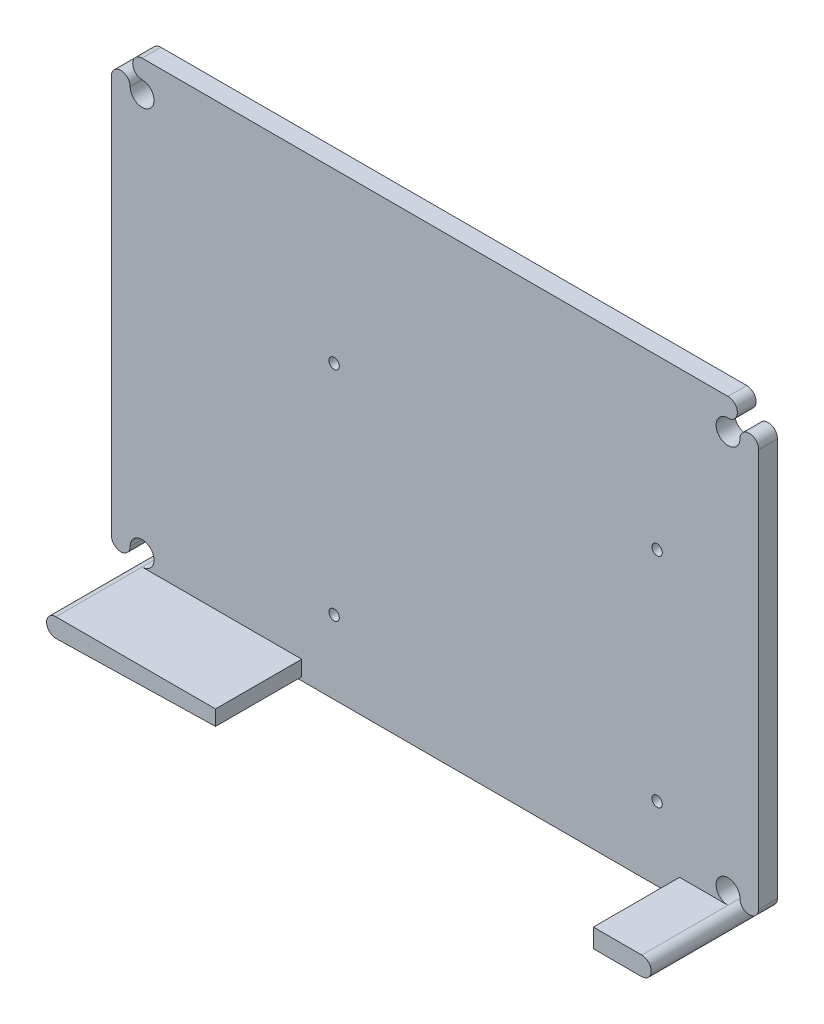
SolidWorks part; units mm, degrees
ref_plane "Plano frontal" through (0, 0, 0) normal (0, 0, 1) x (1, 0, 0)
ref_plane "Plano superior" through (0, 0, 0) normal (0, 1, 0) x (1, 0, 0)
ref_plane "Plano direito" through (0, 0, 0) normal (1, 0, 0) x (0, 0, -1)
sketch "Esboço1" plane through (0, 0, 0) normal (0, 0, 1) x (1, 0, 0)
  line L6 (-78, -61.175) -> (78, -61.175)
  line L10 (-86.175, -53) -> (-86.175, 53)
  line L11 (-78, 61.175) -> (77.9912, 61.175)
  line L12 (86.175, -53) -> (86.175, 53)
  line L13 (-78, -53) -> (78, 53) construction
  line L14 (78, -53) -> (-78, 53) construction
  arc A0 (-81.175, 53) -> (-78, 56.175) centre (-78, 53) ccw
  arc A1 (-78, -56.175) -> (-81.175, -53) centre (-78, -53) ccw
  arc A2 (81.175, -53) -> (78, -56.175) centre (78, -53) ccw
  arc A3 (77.9966, 56.175) -> (81.175, 53) centre (78, 53) ccw
  arc A4 (81.175, 53) -> (86.175, 53) centre (83.675, 53) cw
  arc A5 (77.9966, 56.175) -> (77.9912, 61.175) centre (77.9939, 58.675) ccw
  arc A6 (86.175, -53) -> (81.175, -53) centre (83.675, -53) cw
  arc A7 (78, -56.175) -> (78, -61.175) centre (78, -58.675) cw
  arc A8 (-78, -56.175) -> (-78, -61.175) centre (-78, -58.675) ccw
  arc A9 (-81.175, -53) -> (-86.175, -53) centre (-83.675, -53) cw
  arc A10 (-86.175, 53) -> (-81.175, 53) centre (-83.675, 53) cw
  arc A11 (-78, 56.175) -> (-78, 61.175) centre (-78, 58.675) cw
  point P0 (0, 0)
  point P1 (0, 0)
  point P2 (0, 0)
  point P3 (0, 0)
  point P4 (0, 0)
  point P36 (78.4328, -50.0994)
  dimension "D3" = 3.175
  dimension "D4" = 106
  dimension "D5" = 5
  dimension "D6" = 5
  dimension "D7" = 5
  dimension "D1" = 2.5
  dimension "D2" = 156
  dimension "D8" = 5
  dimension "D9" = 5
  dimension "D10" = 5
  dimension "D11" = 5
  dimension "D12" = 5
  dimension "D13" = 8.0257
  dimension "D14" = 8.0257
  dimension "D15" = 8.03
extrude "Ressalto-extrusão1" add sketch "Esboço1" along normal blind 5
sketch "Esboço2" plane through (0, 0, 5) normal (0, 0, 1) x (1, 0, 0)
  line L0 (-78, -56.175) -> (-35.5, -56.175)
  line L3 (-35.5, -56.175) -> (-35.5, -60.2122)
  line L5 (-35.5, -60.2122) -> (-78, -61.175)
  line L8 (78, -61.175) -> (65.0993, -61.175)
  line L9 (78, -56.175) -> (65.0993, -56.175)
  line L10 (65.0993, -56.175) -> (65.0993, -61.175)
  arc A0 (-78, -56.175) -> (-78, -61.175) centre (-78, -58.675) ccw
  arc A2 (78, -56.175) -> (78, -61.175) centre (78, -58.675) cw
  point P14 (-80.5, -58.675)
  dimension "D1" = 2.5
  dimension "D2" = 12.9007
  dimension "D3" = 45
extrude "Ressalto-extrusão2" add sketch "Esboço2" along normal blind 22.95
sketch "Esboço3" plane through (0, 0, 5) normal (0, 0, 1) x (1, 0, 0)
  line L0 (86.175, -53) -> (86.175, 53) construction
  line L1 (-78, -61.175) -> (65.0993, -61.175) construction
  circle A0 centre (59.1253, -41.6378) radius 1.38
  circle A1 centre (59.1253, 16.3622) radius 1.38
  circle A2 centre (-26.8747, -41.6378) radius 1.38
  circle A3 centre (-26.8747, 16.3622) radius 1.38
  dimension "D1" = 27.0497
  dimension "D2" = 19.5372
  dimension "D3" = 2.76
  dimension "D4" = 86
  dimension "D5" = 58
extrude "Corte-extrusão1" cut sketch "Esboço3" against normal blind 5
